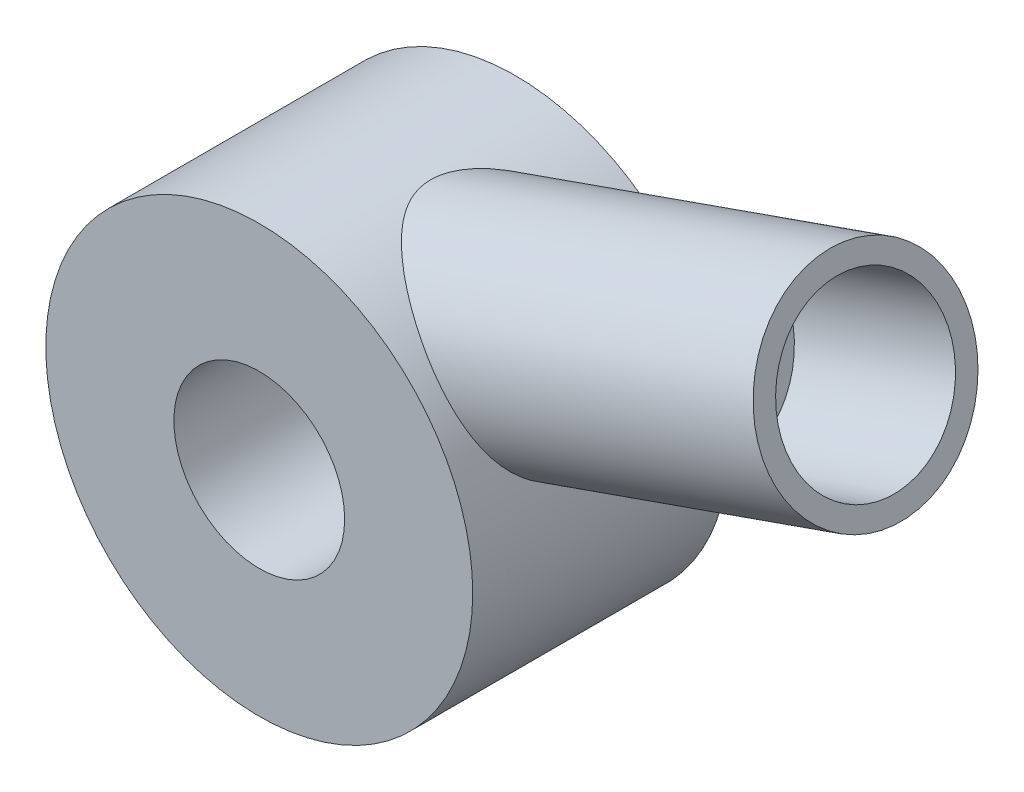
SolidWorks part; units mm, degrees
ref_plane "Front Plane" through (0, 0, 0) normal (0, 0, 1) x (1, 0, 0)
ref_plane "Top Plane" through (0, 0, 0) normal (0, 1, 0) x (1, 0, 0)
ref_plane "Right Plane" through (0, 0, 0) normal (1, 0, 0) x (0, 0, -1)
sketch "Sketch1" plane through (0, 0, 0) normal (0, 0, 1) x (1, 0, 0)
  circle A0 centre (0, 0) radius 63.5
  dimension "D1" = 127
extrude "Boss-Extrude1" add sketch "Sketch1" along normal blind 76.2
sketch "Sketch2" plane through (0, 0, 76.2) normal (0, 0, 1) x (1, 0, 0)
  circle A0 centre (0, 0) radius 25.4
  dimension "D1" = 50.8
extrude "Cut-Extrude1" cut sketch "Sketch2" against normal blind 38.1
sketch "Sketch3" plane through (0, 0, 76.2) normal (0, 0, 1) x (1, 0, 0)
  line L0 (0, 63.5) -> (129.6497, 109.8643)
  line L1 (63.2862, 5.206) -> (138.7566, 32.1951)
  line L2 (129.6497, 109.8643) -> (154.8697, 38.1029)
  line L3 (154.8697, 38.1029) -> (138.7566, 32.1951)
  circle A0 centre (0, 0) radius 63.5 construction
  arc A1 (63.2862, 5.206) -> (0, 63.5) centre (0, 0) ccw
  point P7 (0, 0)
  point P8 (0, 0)
  point P9 (0, 0)
  point P10 (0, 0)
  point P15 (0, 0)
  point P16 (0, 0)
  dimension "D2" = 76.2
extrude "Boss-Extrude2" add sketch "Sketch3" against normal blind 76.2
sketch "Sketch4" plane through (149.7631, 52.6332, 0) normal (0.9434, 0.3316, 0) x (0, 0, -1)
  line L8 (-78.74, 63.2025) -> (-78.74, -17.9416)
  line L9 (-78.74, -17.9416) -> (2.54, -17.9416)
  line L10 (2.54, -17.9416) -> (2.54, 63.2025)
  line L11 (2.54, 63.2025) -> (-78.74, 63.2025)
  line L12 (-78.74, 63.2025) -> (-78.74, -17.9416)
  line L13 (-78.74, -17.9416) -> (2.54, -17.9416)
  line L14 (2.54, -17.9416) -> (2.54, 63.2025)
  line L15 (2.54, 63.2025) -> (-78.74, 63.2025)
  circle A0 centre (-38.1, 22.6305) radius 31.75
  dimension "D1" = 63.5
  dimension "D2" = 2.54
extrude "Cut-Extrude2" cut sketch "Sketch4" against normal up to surface (125.9553 mm away)
sketch "Sketch5" plane through (149.7631, 52.6332, 0) normal (0.9434, 0.3316, 0) x (0, 0, -1)
  circle A0 centre (-38.1, 22.6305) radius 25.4
  dimension "D1" = 50.8
extrude "Cut-Extrude3" cut sketch "Sketch5" against normal blind 50.8
